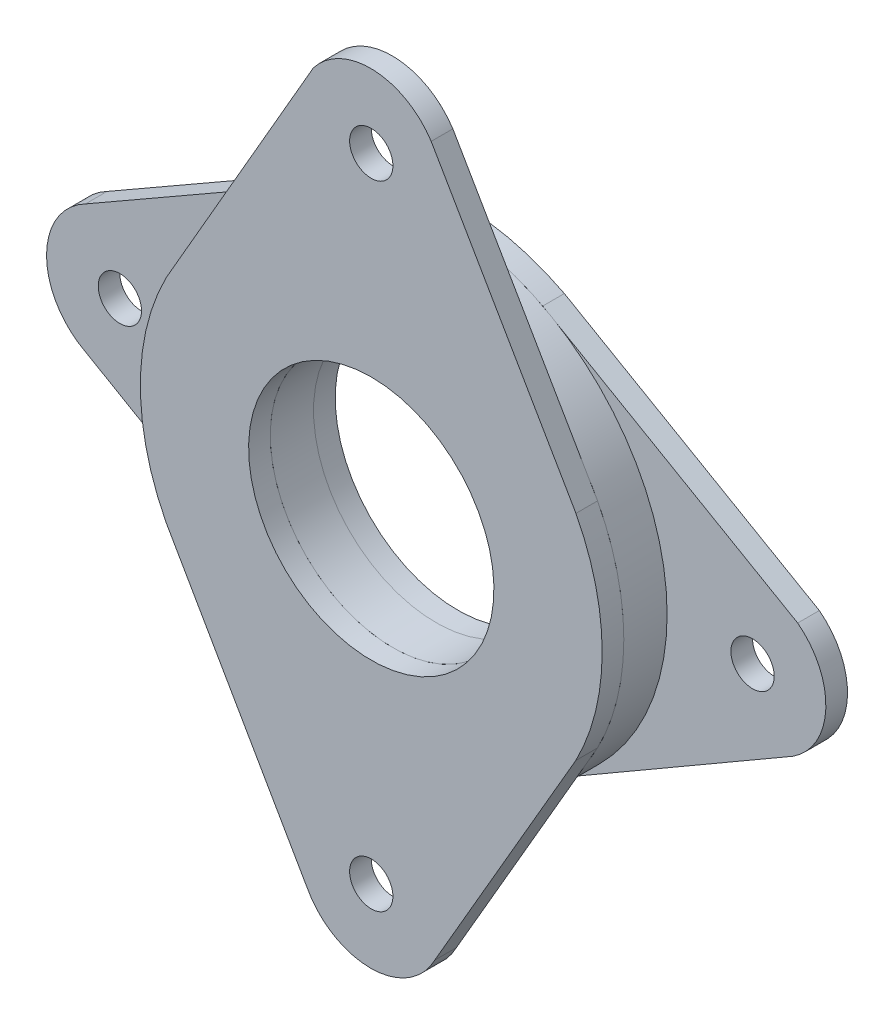
SolidWorks part; units mm, degrees
ref_plane "Front Plane" through (0, 0, 0) normal (0, 0, 1) x (1, 0, 0)
ref_plane "Top Plane" through (0, 0, 0) normal (0, 1, 0) x (1, 0, 0)
ref_plane "Right Plane" through (0, 0, 0) normal (1, 0, 0) x (0, 0, -1)
sketch "Sketch1" plane through (0, 0, 0) normal (0, 0, 1) x (1, 0, 0)
  line L1 (7.3794, 14.1966) -> (25.0466, 4.0094)
  line L2 (-24.3098, 4.4793) -> (-7.325, 14.2248)
  line L3 (-24.3029, -4.3932) -> (-7.4267, -14.1719)
  line L4 (7.408, -14.1817) -> (24.7169, -4.1525)
  line L7 (20.4006, 0) -> (41.1933, 0) construction
  arc A0 (-7.4267, -14.1719) -> (7.408, -14.1817) centre (0, 0) ccw construction
  circle A1 centre (0, 0) radius 27 construction
  arc A4 (24.7169, -4.1525) -> (25.0466, 4.0094) centre (22, 0.0449) ccw
  arc A5 (-7.4267, -14.1719) -> (7.408, -14.1817) centre (0, 0) ccw
  arc A6 (-24.3098, 4.4793) -> (-24.3029, -4.3932) centre (-22, 0.0449) ccw
  arc A7 (7.3794, 14.1966) -> (-7.325, 14.2248) centre (0, 0) ccw construction
  arc A8 (7.3794, 14.1966) -> (-7.325, 14.2248) centre (0, 0) ccw
  point P7 (0, 0)
  dimension "D1" = 32
  dimension "D2" = 54
  dimension "D7" = 10
  dimension "D6" = 22
extrude "Boss-Extrude1" add sketch "Sketch1" along normal blind 1.5
sketch "Sketch2" plane through (0, 0, 1.5) normal (0, 0, 1) x (1, 0, 0)
  line L0 (31.1876, 0) -> (-31.1876, 0) construction
  circle A0 centre (-21.92, 0) radius 1.5
  circle A1 centre (21.92, 0) radius 1.5
  circle A2 centre (0, 0) radius 8.5
  point P9 (0, 0)
  point P10 (-22, 0)
  point P11 (22, 0)
  dimension "D1" = 17
  dimension "D2" = 3
  dimension "D3" = 3
  dimension "D4" = 21.92
  dimension "D5" = 21.92
extrude "Cut-Extrude1" cut sketch "Sketch2" against normal through all
ref_plane "Plane1" through (0, 0, 3) normal (0, 0, 1) x (1, 0, 0)
mirror "Mirror2" about plane through (0, 0, 3) normal (0, 0, 1) of bodies 102
move or copy body "Body-Move/Copy1" bodies to move or copy 104 copy no rotation origin (0, 0, 0) rotation axis (0, 0, 1) rotation angle 90
sketch "Sketch3" plane through (0, 0, 3) normal (0, 0, 1) x (1, 0, 0)
  circle A0 centre (0, 0) radius 16
  circle A1 centre (0, 0) radius 8.5
  dimension "D1" = 32
extrude "Boss-Extrude2" add sketch "Sketch3" along normal blind 1.5 and the other way blind 1.5 separate body
